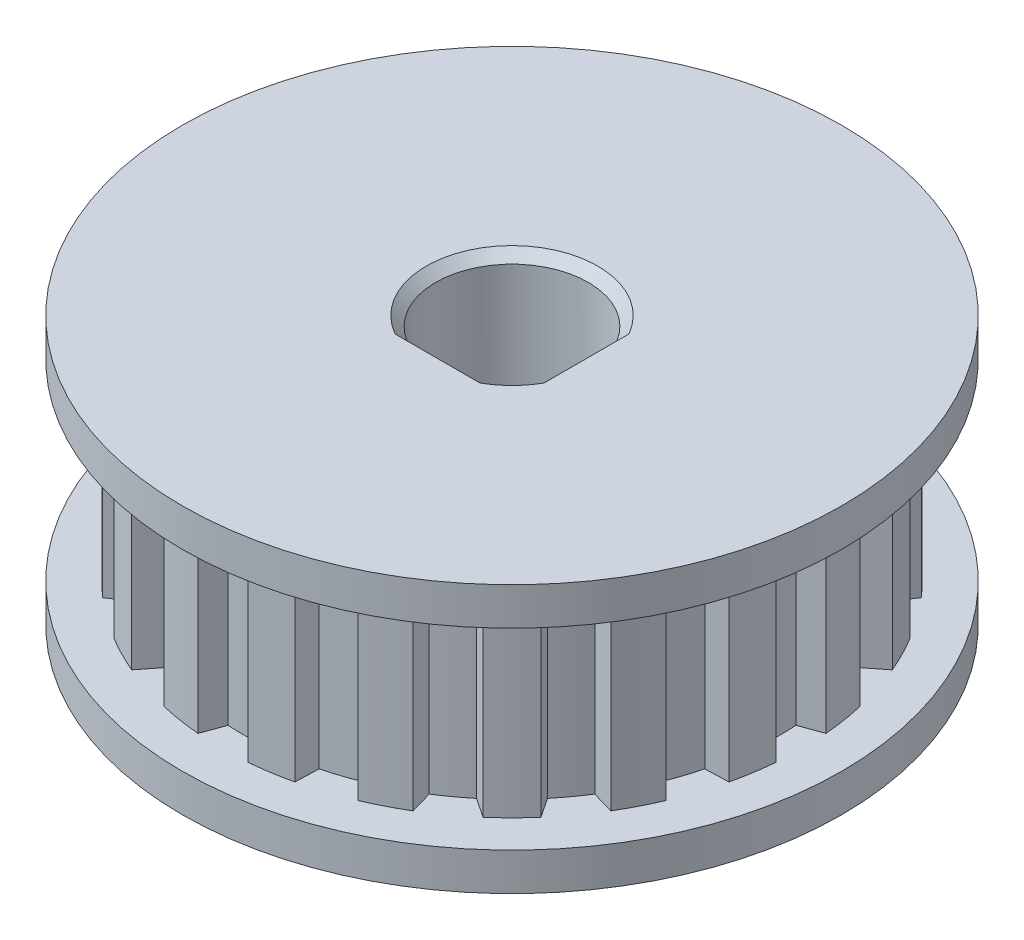
SolidWorks part; units mm, degrees
ref_plane "Спереди" through (0, 0, 0) normal (0, 0, 1) x (1, 0, 0)
ref_plane "Сверху" through (0, 0, 0) normal (0, 1, 0) x (1, 0, 0)
ref_plane "Справа" through (0, 0, 0) normal (1, 0, 0) x (0, 0, -1)
sketch "Эскиз2" plane through (0, 0, 0) normal (0, 1, 0) x (1, 0, 0)
  line L0 (0, 0) -> (0, 16.4) construction
  line L1 (0, 0) -> (2.5655, 16.1981) construction
  line L2 (0, 0) -> (-2.5655, 16.1981) construction
  line L3 (-0.9, 14.1715) -> (-1.3263, 15.3428)
  line L4 (0.9, 14.1715) -> (1.3263, 15.3428)
  line L5 (3.5233, 13.756) -> (3.4798, 15.0017)
  line L6 (5.2352, 13.1997) -> (6.0026, 14.182)
  line L7 (7.6017, 11.994) -> (7.9452, 13.1922)
  line L8 (9.0579, 10.9359) -> (10.0913, 11.633)
  line L9 (10.9359, 9.0579) -> (11.633, 10.0913)
  line L10 (11.994, 7.6017) -> (13.1922, 7.9452)
  line L11 (13.1997, 5.2352) -> (14.182, 6.0026)
  line L12 (13.756, 3.5233) -> (15.0017, 3.4798)
  line L13 (14.1715, 0.9) -> (15.3428, 1.3263)
  line L14 (14.1715, -0.9) -> (15.3428, -1.3263)
  line L15 (13.756, -3.5233) -> (15.0017, -3.4798)
  line L16 (13.1997, -5.2352) -> (14.182, -6.0026)
  line L17 (11.994, -7.6017) -> (13.1922, -7.9452)
  line L18 (10.9359, -9.0579) -> (11.633, -10.0913)
  line L19 (9.0579, -10.9359) -> (10.0913, -11.633)
  line L20 (7.6017, -11.994) -> (7.9452, -13.1922)
  line L21 (5.2352, -13.1997) -> (6.0026, -14.182)
  line L22 (3.5233, -13.756) -> (3.4798, -15.0017)
  line L23 (0.9, -14.1715) -> (1.3263, -15.3428)
  line L24 (-0.9, -14.1715) -> (-1.3263, -15.3428)
  line L25 (-3.5233, -13.756) -> (-3.4798, -15.0017)
  line L26 (-5.2352, -13.1997) -> (-6.0026, -14.182)
  line L27 (-7.6017, -11.994) -> (-7.9452, -13.1922)
  line L28 (-9.0579, -10.9359) -> (-10.0913, -11.633)
  line L29 (-10.9359, -9.0579) -> (-11.633, -10.0913)
  line L30 (-11.994, -7.6017) -> (-13.1922, -7.9452)
  line L31 (-13.1997, -5.2352) -> (-14.182, -6.0026)
  line L32 (-13.756, -3.5233) -> (-15.0017, -3.4798)
  line L33 (-14.1715, -0.9) -> (-15.3428, -1.3263)
  line L34 (-14.1715, 0.9) -> (-15.3428, 1.3263)
  line L35 (-13.756, 3.5233) -> (-15.0017, 3.4798)
  line L36 (-13.1997, 5.2352) -> (-14.182, 6.0026)
  line L37 (-11.994, 7.6017) -> (-13.1922, 7.9452)
  line L38 (-10.9359, 9.0579) -> (-11.633, 10.0913)
  line L39 (-9.0579, 10.9359) -> (-10.0913, 11.633)
  line L40 (-7.6017, 11.994) -> (-7.9452, 13.1922)
  line L41 (-5.2352, 13.1997) -> (-6.0026, 14.182)
  line L42 (-3.5233, 13.756) -> (-3.4798, 15.0017)
  circle A0 centre (0, 0) radius 16.4 construction
  circle A1 centre (0, 0) radius 15.9 construction
  circle A2 centre (0, 0) radius 15.4 construction
  circle A3 centre (0, 0) radius 14.2 construction
  arc A4 (-0.9, 14.1715) -> (0.9, 14.1715) centre (0, 0) cw
  arc A5 (3.5233, 13.756) -> (5.2352, 13.1997) centre (0, 0) cw
  arc A6 (7.6017, 11.994) -> (9.0579, 10.9359) centre (0, 0) cw
  arc A7 (10.9359, 9.0579) -> (11.994, 7.6017) centre (0, 0) cw
  arc A8 (13.1997, 5.2352) -> (13.756, 3.5233) centre (0, 0) cw
  arc A9 (14.1715, 0.9) -> (14.1715, -0.9) centre (0, 0) cw
  arc A10 (13.756, -3.5233) -> (13.1997, -5.2352) centre (0, 0) cw
  arc A11 (11.994, -7.6017) -> (10.9359, -9.0579) centre (0, 0) cw
  arc A12 (9.0579, -10.9359) -> (7.6017, -11.994) centre (0, 0) cw
  arc A13 (5.2352, -13.1997) -> (3.5233, -13.756) centre (0, 0) cw
  arc A14 (0.9, -14.1715) -> (-0.9, -14.1715) centre (0, 0) cw
  arc A15 (-3.5233, -13.756) -> (-5.2352, -13.1997) centre (0, 0) cw
  arc A16 (-7.6017, -11.994) -> (-9.0579, -10.9359) centre (0, 0) cw
  arc A17 (-10.9359, -9.0579) -> (-11.994, -7.6017) centre (0, 0) cw
  arc A18 (-13.1997, -5.2352) -> (-13.756, -3.5233) centre (0, 0) cw
  arc A19 (-14.1715, -0.9) -> (-14.1715, 0.9) centre (0, 0) cw
  arc A20 (-13.756, 3.5233) -> (-13.1997, 5.2352) centre (0, 0) cw
  arc A21 (-11.994, 7.6017) -> (-10.9359, 9.0579) centre (0, 0) cw
  arc A22 (-9.0579, 10.9359) -> (-7.6017, 11.994) centre (0, 0) cw
  arc A23 (-5.2352, 13.1997) -> (-3.5233, 13.756) centre (0, 0) cw
  arc A24 (-3.4798, 15.0017) -> (-1.3263, 15.3428) centre (0, 0) cw
  arc A25 (1.3263, 15.3428) -> (3.4798, 15.0017) centre (0, 0) cw
  arc A26 (6.0026, 14.182) -> (7.9452, 13.1922) centre (0, 0) cw
  arc A27 (10.0913, 11.633) -> (11.633, 10.0913) centre (0, 0) cw
  arc A28 (13.1922, 7.9452) -> (14.182, 6.0026) centre (0, 0) cw
  arc A29 (15.0017, 3.4798) -> (15.3428, 1.3263) centre (0, 0) cw
  arc A30 (15.3428, -1.3263) -> (15.0017, -3.4798) centre (0, 0) cw
  arc A31 (14.182, -6.0026) -> (13.1922, -7.9452) centre (0, 0) cw
  arc A32 (11.633, -10.0913) -> (10.0913, -11.633) centre (0, 0) cw
  arc A33 (7.9452, -13.1922) -> (6.0026, -14.182) centre (0, 0) cw
  arc A34 (3.4798, -15.0017) -> (1.3263, -15.3428) centre (0, 0) cw
  arc A35 (-1.3263, -15.3428) -> (-3.4798, -15.0017) centre (0, 0) cw
  arc A36 (-6.0026, -14.182) -> (-7.9452, -13.1922) centre (0, 0) cw
  arc A37 (-10.0913, -11.633) -> (-11.633, -10.0913) centre (0, 0) cw
  arc A38 (-13.1922, -7.9452) -> (-14.182, -6.0026) centre (0, 0) cw
  arc A39 (-15.0017, -3.4798) -> (-15.3428, -1.3263) centre (0, 0) cw
  arc A40 (-15.3428, 1.3263) -> (-15.0017, 3.4798) centre (0, 0) cw
  arc A41 (-14.182, 6.0026) -> (-13.1922, 7.9452) centre (0, 0) cw
  arc A42 (-11.633, 10.0913) -> (-10.0913, 11.633) centre (0, 0) cw
  arc A43 (-7.9452, 13.1922) -> (-6.0026, 14.182) centre (0, 0) cw
  point P11 (0, 14.2)
  dimension "D1" = 32.8
  dimension "D2" = 31.8
  dimension "D3" = 30.8
  dimension "D4" = 28.4
  dimension "D7" = 1.8
  dimension "D5" = 9
  dimension "D6" = 9
  dimension "D8" = 20
  dimension "D9" = 20
extrude "Вытянуть1" add sketch "Эскиз2" along normal blind 10.2
sketch "Эскиз3" plane through (0, 10.2, 0) normal (0, 1, 0) x (1, 0, 0)
  circle A0 centre (0, 0) radius 17.5
  dimension "D1" = 35
extrude "Вытянуть2" add sketch "Эскиз3" along normal blind 2
sketch "Эскиз4" plane through (0, 0, 0) normal (0, -1, 0) x (1, 0, 0)
  circle A0 centre (0, 0) radius 17.5
  circle A1 centre (0, 0) radius 17.5 construction
extrude "Вытянуть3" add sketch "Эскиз4" along normal blind 2
sketch "Эскиз5" plane through (0, 12.2, 0) normal (0, 1, 0) x (1, 0, 0)
  line L0 (3.45, -2.1213) -> (3.45, 2.1213)
  line L1 (2.1213, -3.45) -> (-2.1213, -3.45)
  circle A0 centre (0, 0) radius 4.05 construction
  arc A1 (2.1213, -3.45) -> (3.45, -2.1213) centre (0, 0) ccw
  arc A2 (-2.1213, -3.45) -> (3.45, 2.1213) centre (0, 0) cw
  dimension "D1" = 8.1
  dimension "D2" = 3.45
  dimension "D3" = 3.45
extrude "Вытянуть4" cut sketch "Эскиз5" against normal blind 10
sketch "Эскиз6" plane through (0, -2, 0) normal (0, -1, 0) x (1, 0, 0)
  circle A0 centre (0, 0) radius 4.05
  dimension "D1" = 8.1
extrude "Вытянуть5" cut sketch "Эскиз6" against normal up to surface (4.2 mm away) up to face at (0.8625, 2.2, 0.8625)
chamfer "Фаска1" distance 0.5 angle 45 4 edges at (3.45, 12.2, 0) (-2.8638, 12.2, -2.8638) (2.8638, 12.2, 2.8638) (0, 12.2, 3.45)
chamfer "Фаска2" distance 0.5 angle 45 1 edges at (0, -2, -4.05)
